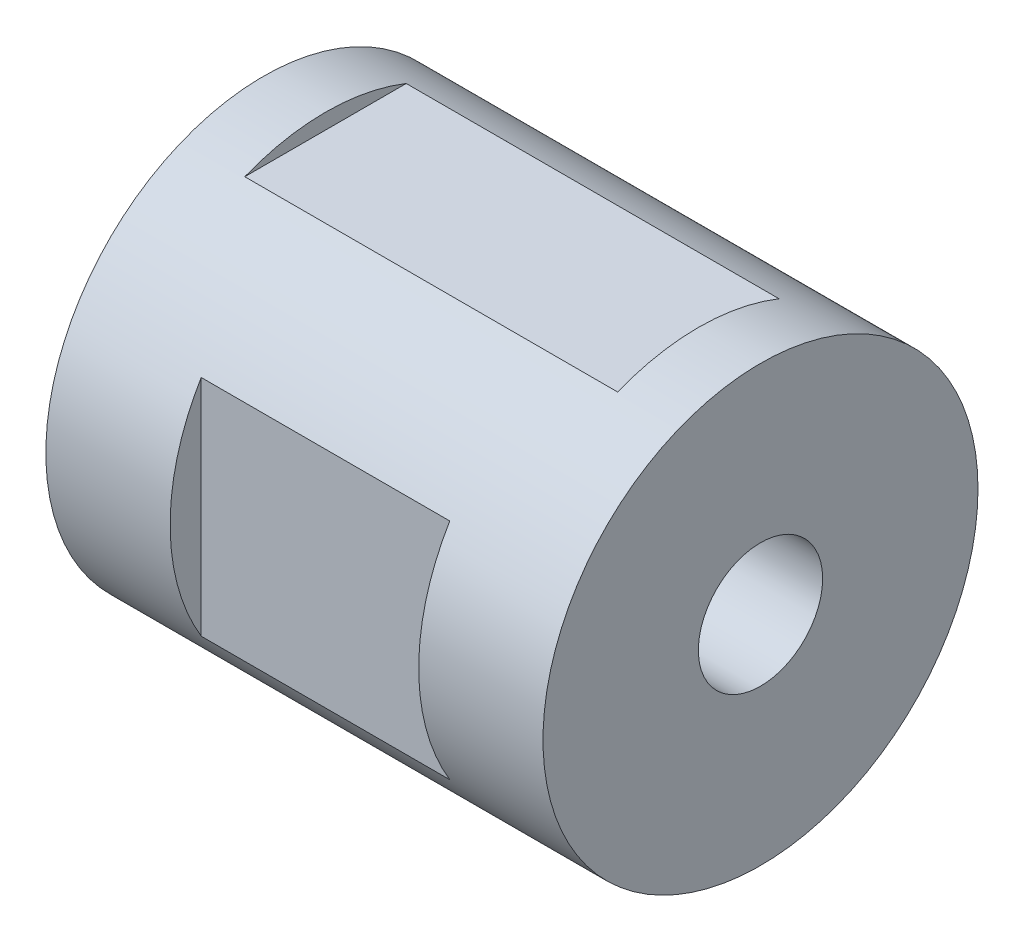
SolidWorks part; units mm, degrees
ref_plane "Front Plane" through (0, 0, 0) normal (0, 0, 1) x (1, 0, 0)
ref_plane "Top Plane" through (0, 0, 0) normal (0, 1, 0) x (1, 0, 0)
ref_plane "Right Plane" through (0, 0, 0) normal (1, 0, 0) x (0, 0, -1)
sketch "Sketch1" plane through (0, 0, 0) normal (1, 0, 0) x (0, 0, -1)
  circle A0 centre (0, 0) radius 889
  circle A1 centre (0, 0) radius 254
  dimension "D1" = 1778
  dimension "D2" = 508
extrude "Boss-Extrude1" add sketch "Sketch1" against normal blind 2032
ref_plane "Plane1" through (0, 0, 889) normal (0, 0, 1) x (1, 0, 0)
sketch "Sketch2" plane through (0, 0, 889) normal (0, 0, 1) x (1, 0, 0)
  line L0 (-2032, 889) -> (0, 889) construction
  line L1 (-508, 457.962) -> (-1524, 457.962)
  line L2 (-508, 457.962) -> (-508, -457.962)
  line L3 (-508, -457.962) -> (-1524, -457.962)
  line L4 (-1524, 457.962) -> (-1524, -457.962)
  line L5 (-508, 457.962) -> (-1524, -457.962) construction
  line L6 (-508, -457.962) -> (-1524, 457.962) construction
  line L8 (-2032, -889) -> (0, -889) construction
  point P0 (-1016, 0)
  point P5 (-1016, 889)
  dimension "D1" = 1016
  dimension "D2" = 915.924
extrude "Cut-Extrude1" cut sketch "Sketch2" against normal blind 127
ref_plane "Plane2" through (0, 889, 0) normal (0, 1, 0) x (1, 0, 0)
sketch "Sketch3" plane through (0, 889, 0) normal (0, 1, 0) x (1, 0, 0)
  line L0 (-2032, 889) -> (0, 889) construction
  line L1 (-254, 329.946) -> (-1778, 329.946)
  line L2 (-254, 329.946) -> (-254, -329.946)
  line L3 (-254, -329.946) -> (-1778, -329.946)
  line L4 (-1778, 329.946) -> (-1778, -329.946)
  line L5 (-254, 329.946) -> (-1778, -329.946) construction
  line L6 (-254, -329.946) -> (-1778, 329.946) construction
  point P0 (-1016, 0)
  point P5 (-1016, 329.946)
  point P11 (-1016, 889)
  dimension "D1" = 1524
  dimension "D2" = 659.892
extrude "Cut-Extrude2" cut sketch "Sketch3" against normal blind 63.5
